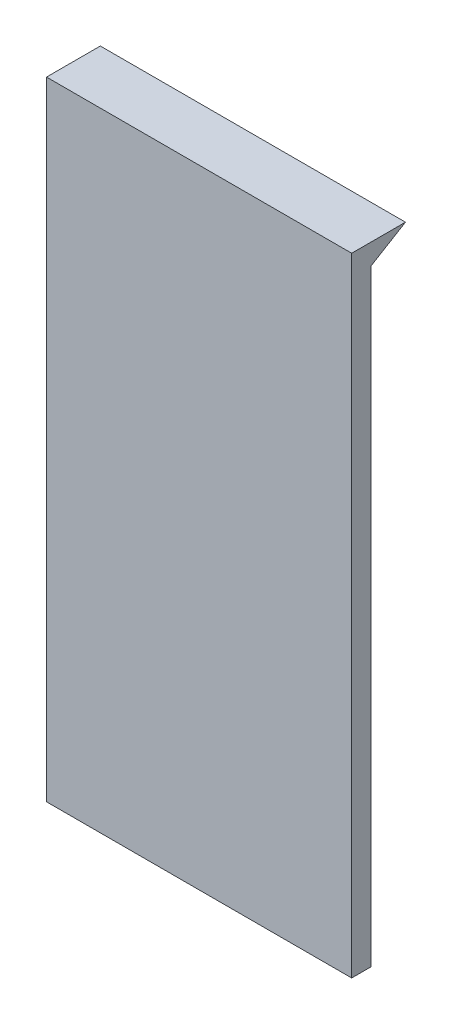
SolidWorks part; units mm, degrees
material "ABS"
ref_plane "Plan de face" through (0, 0, 0) normal (0, 0, 1) x (1, 0, 0)
ref_plane "Plan de dessus" through (0, 0, 0) normal (0, 1, 0) x (1, 0, 0)
ref_plane "Plan de droite" through (0, 0, 0) normal (1, 0, 0) x (0, 0, -1)
sketch "Esquisse1" plane through (0, 0, 0) normal (0, 0, 1) x (1, 0, 0)
  line L1 (0, 0) -> (47, 0)
  line L2 (0, 0) -> (0, 93.5)
  line L3 (0, 93.5) -> (47, 93.5)
  line L4 (47, 0) -> (47, 93.5)
  dimension "D1" = 93.5
  dimension "D2" = 47
extrude "Boss.-Extru.1" add sketch "Esquisse1" against normal blind 3
sketch "Esquisse2" plane through (47, 0, 0) normal (1, 0, 0) x (0, 0, -1)
  line L0 (3, 93.5) -> (8.2841, 96.675)
  line L1 (8.2841, 96.675) -> (0, 96.675)
  line L2 (0, 96.675) -> (0, 93.5)
  line L3 (0, 93.5) -> (3, 93.5)
  line L6 (0, 0) -> (0, 93.5) construction
  dimension "D1" = 59
  dimension "D2" = 3.175
extrude "Boss.-Extru.2" add sketch "Esquisse2" against normal up to surface (47 mm away) up to face at (0, 46.75, -1.5)
